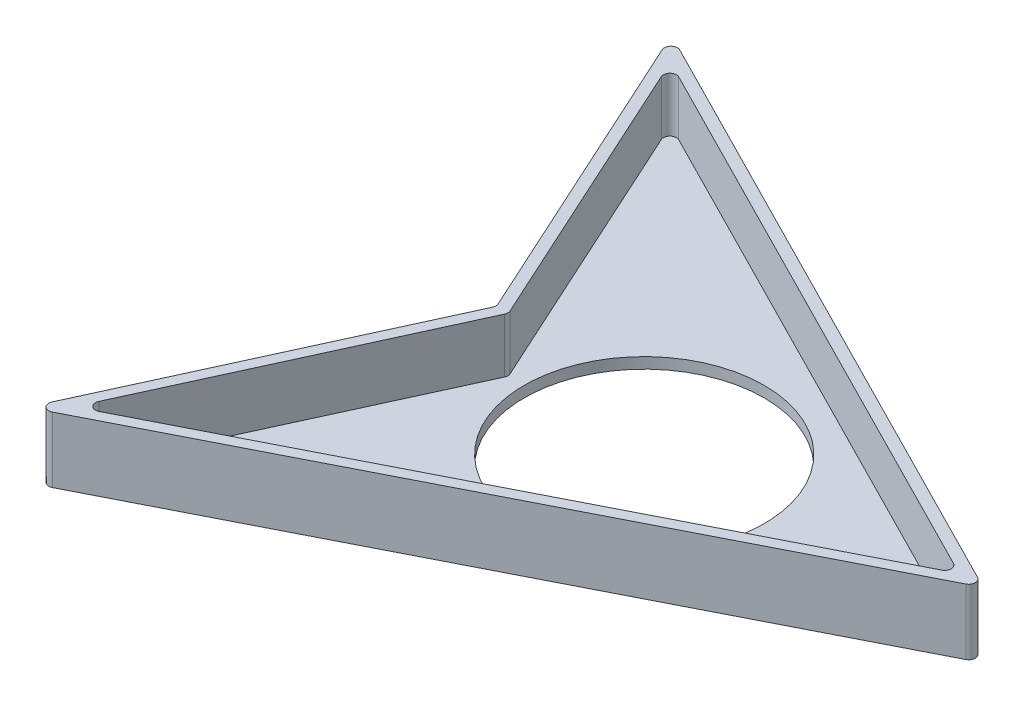
SolidWorks part; units mm, degrees
ref_plane "Alzado" through (0, 0, 0) normal (0, 0, 1) x (1, 0, 0)
ref_plane "Planta" through (0, 0, 0) normal (0, 1, 0) x (1, 0, 0)
ref_plane "Vista lateral" through (0, 0, 0) normal (1, 0, 0) x (0, 0, -1)
sketch "Croquis2" plane through (0, 0, 0) normal (0, 1, 0) x (1, 0, 0)
  line L0 (2.7471, -570.0977) -> (52.4543, -570.0977) construction
  line L1 (0, 0) -> (20, 0) construction
  line L2 (20, 0) -> (-6.05, 13.2393) construction
  line L3 (-6.05, 13.2393) -> (0, 0) construction
  line L4 (20, 0) -> (-6.05, -13.2393) construction
  line L5 (-6.05, -13.2393) -> (0, 0) construction
  line L6 (-6.4699, 13.6771) -> (-0.2199, 0)
  line L7 (-6.4699, -13.6771) -> (-0.2199, 0)
  line L8 (20.4414, 0) -> (-6.4699, -13.6771)
  line L9 (20.4414, 0) -> (-6.4699, 13.6771)
  circle A0 centre (6, 0) radius 5.5 construction
  dimension "D2" = 11
  dimension "D3" = 14
  dimension "D1" = 20
  dimension "D4" = 38.5
  dimension "D5" = 6.05
  dimension "D6" = 0.2
extrude "Saliente-Extruir1" add sketch "Croquis2" along normal blind 2.5
shell "Vaciado1" thickness 0.5
sketch "Croquis3" plane through (0, 0, 0) normal (0, 1, 0) x (1, 0, 0)
  circle A0 centre (6, 0) radius 5.5
  point P2 (0, 0)
  dimension "D1" = 11
  dimension "D2" = 6
extrude "Cortar-Extruir1" cut sketch "Croquis3" against normal through all
fillet "Redondeo1" radius 0.3 8 edges at (-7.5198, 1, 14.7716) (-7.5198, 1, -14.7716) (-0.7696, 1, 0) (21.545, 1, 0) (-6.4699, 1.25, 13.6771) (20.4414, 1.25, 0) (-0.2199, 1.25, 0) (-6.4699, 1.25, -13.6771)
